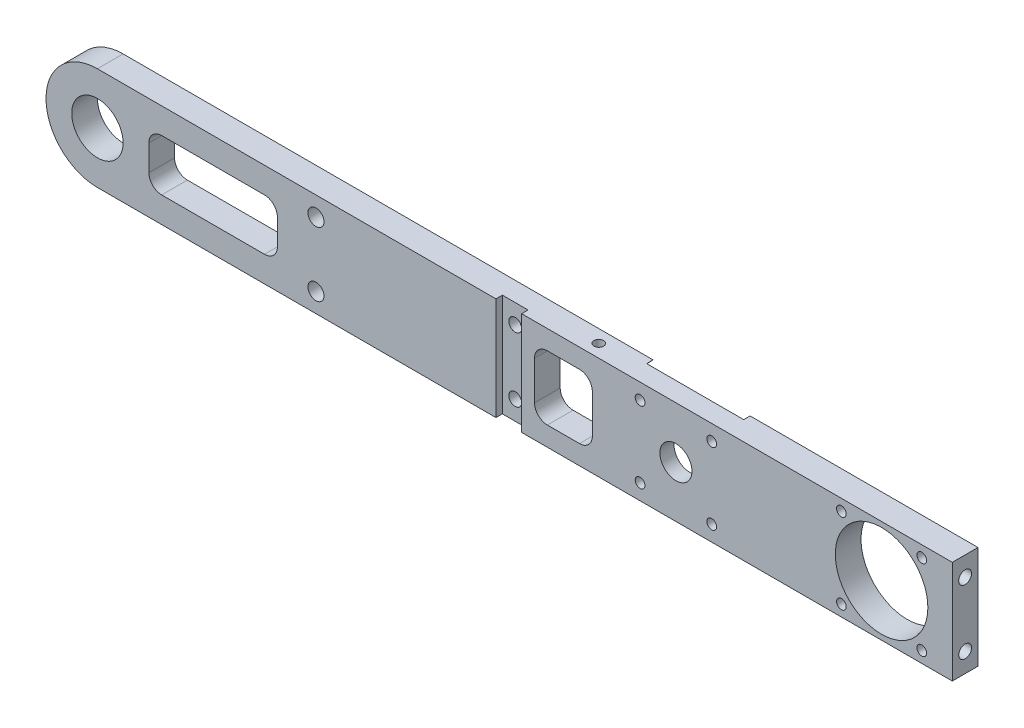
SolidWorks part; units mm, degrees
material "6061 Alloy"
ref_plane "Front Plane" through (0, 0, 0) normal (0, 0, 1) x (1, 0, 0)
ref_plane "Top Plane" through (0, 0, 0) normal (0, 1, 0) x (1, 0, 0)
ref_plane "Right Plane" through (0, 0, 0) normal (1, 0, 0) x (0, 0, -1)
sketch "Sketch1" plane through (0, 0, 0) normal (0, 0, 1) x (1, 0, 0)
  line L0 (0, 50.8) -> (-422.275, 50.8)
  line L1 (0, 50.8) -> (0, 0)
  line L2 (0, 0) -> (-422.275, 0)
  arc A0 (-422.275, 50.8) -> (-422.275, 0) centre (-422.275, 25.4) ccw
  circle A1 centre (-422.275, 25.4) radius 12.7
  circle A2 centre (-136.525, 25.4) radius 7.9375
  circle A3 centre (-34.925, 25.4) radius 22.86
  dimension "D3" = 25.4
  dimension "D6" = 15.875
  dimension "D7" = 45.72
  dimension "D1" = 50.8
  dimension "D2" = 422.275
  dimension "D4" = 136.525
  dimension "D5" = 25.4
  dimension "D8" = 34.925
  dimension "D9" = 25.4
extrude "Extrude1" add sketch "Sketch1" along normal blind 12.7
sketch "Sketch2" plane through (0, 0, 12.7) normal (0, 0, 1) x (1, 0, 0)
  line L0 (0, 50.8) -> (-422.275, 50.8) construction
  line L1 (-212.725, 50.8) -> (-225.425, 50.8)
  line L2 (-212.725, 50.8) -> (-212.725, 0)
  line L3 (-212.725, 0) -> (-225.425, 0)
  line L4 (-225.425, 50.8) -> (-225.425, 0)
  line L5 (-422.275, 0) -> (0, 0) construction
  line L6 (0, 0) -> (0, 50.8) construction
  dimension "D1" = 12.7
  dimension "D2" = 212.725
extrude "Cut-Extrude1" cut sketch "Sketch2" against normal blind 3.175
sketch "Sketch4" plane through (0, 0, 0) normal (0, 0, -1) x (-1, 0, 0)
  circle A0 centre (136.525, 25.4) radius 34.925
  dimension "D1" = 69.85
extrude "Cut-Extrude3" cut sketch "Sketch4" against normal blind 3.175
sketch "Sketch5" plane through (0, 0, 3.175) normal (0, 0, -1) x (-1, 0, 0)
  circle A0 centre (136.525, 25.4) radius 17.4625
  dimension "D1" = 34.925
extrude "Cut-Extrude4" cut sketch "Sketch5" against normal blind 2.54
sketch "Sketch6" plane through (0, 0, 12.7) normal (0, 0, 1) x (1, 0, 0)
  line L0 (0, 50.8) -> (-212.725, 50.8) construction
  line L1 (-390.525, 38.1) -> (-339.725, 38.1)
  line L2 (-396.875, 31.75) -> (-396.875, 19.05)
  line L3 (-390.525, 12.7) -> (-339.725, 12.7)
  line L4 (-333.375, 31.75) -> (-333.375, 19.05)
  line L5 (-160.4957, 50.8) -> (-422.275, 50.8) construction
  line L9 (-266.7, 41.275) -> (-238.125, 41.275)
  line L10 (-273.05, 34.925) -> (-273.05, 15.875)
  line L11 (-266.7, 9.525) -> (-238.125, 9.525)
  line L12 (-231.775, 34.925) -> (-231.775, 15.875)
  line L13 (-200.025, 41.275) -> (-184.15, 41.275)
  line L14 (-206.375, 34.925) -> (-206.375, 15.875)
  line L15 (-200.025, 9.525) -> (-184.15, 9.525)
  line L16 (-177.8, 34.925) -> (-177.8, 15.875)
  line L17 (-212.725, 0) -> (-212.725, 50.8) construction
  line L18 (-422.275, 0) -> (-225.425, 0) construction
  line L19 (-225.425, 50.8) -> (-225.425, 0) construction
  arc A0 (-184.15, 41.275) -> (-177.8, 34.925) centre (-184.15, 34.925) cw
  arc A1 (-184.15, 9.525) -> (-177.8, 15.875) centre (-184.15, 15.875) ccw
  arc A2 (-206.375, 15.875) -> (-200.025, 9.525) centre (-200.025, 15.875) ccw
  arc A3 (-200.025, 41.275) -> (-206.375, 34.925) centre (-200.025, 34.925) ccw
  arc A4 (-238.125, 41.275) -> (-231.775, 34.925) centre (-238.125, 34.925) cw
  arc A5 (-238.125, 9.525) -> (-231.775, 15.875) centre (-238.125, 15.875) ccw
  arc A6 (-273.05, 15.875) -> (-266.7, 9.525) centre (-266.7, 15.875) ccw
  arc A7 (-266.7, 41.275) -> (-273.05, 34.925) centre (-266.7, 34.925) ccw
  arc A12 (-339.725, 38.1) -> (-333.375, 31.75) centre (-339.725, 31.75) cw
  arc A13 (-339.725, 12.7) -> (-333.375, 19.05) centre (-339.725, 19.05) ccw
  arc A14 (-396.875, 19.05) -> (-390.525, 12.7) centre (-390.525, 19.05) ccw
  arc A15 (-390.525, 38.1) -> (-396.875, 31.75) centre (-390.525, 31.75) ccw
  circle A16 centre (-422.275, 25.4) radius 12.7 construction
  dimension "D5" = 6.35
  dimension "D6" = 6.35
  dimension "D14" = 25.4
  dimension "D1" = 28.575
  dimension "D2" = 31.75
  dimension "D3" = 9.525
  dimension "D4" = 6.35
  dimension "D7" = 41.275
  dimension "D8" = 31.75
  dimension "D9" = 12.7
  dimension "D10" = 25.4
  dimension "D11" = 9.525
  dimension "D12" = 6.35
  dimension "D13" = 63.5
extrude "Cut-Extrude5" cut sketch "Sketch6" against normal through all
sketch "Sketch7" plane through (0, 0, 0) normal (0, 0, -1) x (-1, 0, 0)
  line L1 (0, 0) -> (0, 50.8) construction
  line L2 (112.5543, 0) -> (0, 0) construction
  circle A0 centre (80.9625, 31.75) radius 12.7
  dimension "D1" = 25.4
  dimension "D2" = 31.75
  dimension "D3" = 80.9625
extrude "Cut-Extrude6" cut sketch "Sketch7" against normal blind 9.525
sketch "Sketch8" plane through (0, 0, 3.175) normal (0, 0, -1) x (-1, 0, 0)
  line L0 (136.525, 25.4) -> (118.8339, 43.0911) construction
  line L1 (0, 50.8) -> (112.5543, 50.8) construction
  circle A0 centre (118.8339, 43.0911) radius 2.413
  circle A2 centre (136.525, 25.4) radius 7.9375 construction
  dimension "D1" = 4.826
  dimension "D2" = 25.019
  dimension "D3" = 45
extrude "Cut-Extrude7" cut sketch "Sketch8" against normal through all
pattern_circular "CirPattern1" count 4 over 360 about axis through (-136.525, 25.4, 0) along (0, 0, 1) of "Cut-Extrude7"
sketch "Sketch9" plane through (0, 0, 0) normal (0, 0, -1) x (-1, 0, 0)
  line L0 (0, 50.8) -> (112.5543, 50.8) construction
  line L1 (0, 0) -> (0, 50.8) construction
  circle A0 centre (15.0812, 45.2437) radius 2.3812
  circle A1 centre (54.7687, 45.2437) radius 2.3812
  circle A2 centre (54.7687, 5.5562) radius 2.3812
  circle A3 centre (15.0813, 5.5562) radius 2.3813
  dimension "D1" = 4.7625
  dimension "D2" = 39.6875
  dimension "D3" = 39.6875
  dimension "D4" = 5.5562
  dimension "D5" = 15.0812
extrude "Cut-Extrude8" cut sketch "Sketch9" against normal through all
sketch "Sketch10" plane through (0, 0, 0) normal (0, 0, -1) x (-1, 0, 0)
  line L0 (160.4957, 50.8) -> (422.275, 50.8) construction
  circle A0 centre (314.325, 41.275) radius 3.9688
  circle A1 centre (314.325, 9.525) radius 3.9688
  circle A2 centre (422.275, 25.4) radius 12.7 construction
  dimension "D1" = 7.9375
  dimension "D2" = 7.9375
  dimension "D3" = 31.75
  dimension "D4" = 9.525
  dimension "D5" = 107.95
extrude "Cut-Extrude9" cut sketch "Sketch10" against normal through all
sketch "Sketch11" plane through (0, 0, 12.7) normal (0, 0, 1) x (1, 0, 0)
  line L0 (-238.125, 41.275) -> (-266.7, 41.275) construction
  line L1 (-273.05, 41.275) -> (-231.775, 41.275)
  line L2 (-273.05, 41.275) -> (-273.05, 9.525)
  line L3 (-273.05, 9.525) -> (-231.775, 9.525)
  line L4 (-231.775, 41.275) -> (-231.775, 9.525)
  line L5 (-273.05, 34.925) -> (-273.05, 15.875) construction
  line L6 (-231.775, 15.875) -> (-231.775, 34.925) construction
  line L7 (-266.7, 9.525) -> (-238.125, 9.525) construction
extrude "Extrude2" add sketch "Sketch11" against normal blind 3.175
sketch "Sketch12" plane through (0, 0, 0) normal (1, 0, 0) x (0, 0, -1)
  line L1 (-12.7, 0) -> (-12.7, 50.8) construction
  line L2 (-12.7, 50.8) -> (0, 50.8) construction
  line L3 (-12.7, 0) -> (0, 0) construction
  circle A0 centre (-6.35, 9.525) radius 3.175
  circle A1 centre (-6.35, 41.275) radius 3.175
  dimension "D1" = 6.35
  dimension "D2" = 6.35
  dimension "D3" = 6.35
  dimension "D4" = 6.35
  dimension "D5" = 9.525
  dimension "D6" = 9.525
extrude "Cut-Extrude10" cut sketch "Sketch12" against normal up to next
sketch "Sketch13" plane through (0, 0, 9.525) normal (0, 0, 1) x (1, 0, 0)
  line L0 (-212.725, 0) -> (-212.725, 50.8) construction
  line L1 (-225.425, 50.8) -> (-225.425, 0) construction
  line L2 (-212.725, 50.8) -> (-225.425, 50.8) construction
  line L3 (-225.425, 0) -> (-212.725, 0) construction
  circle A0 centre (-219.075, 41.275) radius 3.175
  circle A1 centre (-219.075, 9.525) radius 3.175
  dimension "D1" = 6.35
  dimension "D2" = 6.35
  dimension "D3" = 6.35
  dimension "D4" = 6.35
  dimension "D5" = 9.525
  dimension "D6" = 9.525
extrude "Cut-Extrude11" cut sketch "Sketch13" against normal through all
sketch "Sketch14" plane through (0, 0, 0) normal (0, 0, -1) x (-1, 0, 0)
  circle A0 centre (219.075, 41.275) radius 6.7437
  circle A1 centre (219.075, 9.525) radius 6.7437
  dimension "D1" = 13.4874
  dimension "D2" = 13.4874
extrude "Cut-Extrude12" cut sketch "Sketch14" against normal through all draft 41
sketch "Sketch15" plane through (0, 50.8, 0) normal (0, 1, 0) x (-1, 0, 0)
  line L1 (0, 12.7) -> (212.725, 12.7) construction
  line L3 (0, 12.7) -> (0, 0) construction
  circle A1 centre (180.975, 6.35) radius 2.3813
  dimension "D1" = 4.7625
  dimension "D2" = 180.975
  dimension "D5" = 6.35
extrude "Cut-Extrude13" cut sketch "Sketch15" against normal blind 15.875
sketch "Sketch16" plane through (0, 0, 0) normal (0, -1, 0) x (1, 0, 0)
  circle A1 centre (-180.975, 6.35) radius 2.3813
  circle A3 centre (-180.975, 6.35) radius 2.3813 construction
  dimension "D2" = 4.7625
extrude "Cut-Extrude14" cut sketch "Sketch16" against normal blind 15.875
sketch "Sketch17" plane through (0, 0, 0) normal (0, 0, -1) x (-1, 0, 0)
  line L0 (317.5, 50.8) -> (274.7242, 177.103)
  line L1 (160.4957, 50.8) -> (422.275, 50.8) construction
  line L2 (274.7242, 177.103) -> (250.6665, 168.9553)
  line L3 (250.6665, 168.9553) -> (271.0359, 108.811)
  line L4 (317.5, 50.8) -> (250.6665, 50.8)
  line L5 (0, 0) -> (0, 50.8) construction
  line L6 (271.0359, 108.811) -> (250.6665, 50.8)
  dimension "D1" = 317.5
  dimension "D2" = 25.4
  dimension "D3" = 71.29
  dimension "D4" = 133.35
  dimension "D5" = 63.5
extrude "Extrude3" [suppressed] add sketch "Sketch17" against normal up to surface (12.7 mm away)
sketch "Sketch18" [suppressed] plane through (0, 0, 0) normal (0, 0, -1) x (-1, 0, 0)
  line L0 (284.4698, 108.7362) -> (264.1267, 50.8)
  line L1 (264.1267, 50.8) -> (304.0914, 50.8)
  line L2 (304.0914, 50.8) -> (284.4698, 108.7362)
  line L3 (317.5, 50.8) -> (274.7242, 177.103) construction
  line L4 (271.0359, 108.811) -> (250.6665, 50.8) construction
  line L5 (317.5, 50.8) -> (422.275, 50.8) construction
  dimension "D1" = 12.7
  dimension "D2" = 12.7
extrude "Cut-Extrude15" [suppressed] cut sketch "Sketch18" against normal through all
ref_plane "Plane1" through (0, 25.4, 0) normal (0, 1, 0) x (-1, 0, 0)
mirror "Mirror6" [suppressed] about plane through (0, 25.4, 0) normal (0, 1, 0)
fillet "Fillet1" [suppressed] radius 25.4
fillet "Fillet2" [suppressed] radius 12.7
fillet "Fillet4" [suppressed] radius 6.35
fillet "Fillet3" [suppressed] radius 12.7
sketch "Sketch19" [suppressed] plane through (0, 0, 0) normal (0, 0, -1) x (-1, 0, 0)
  line L0 (271.717, -125.2846) -> (253.6737, -119.1737) construction
  line L1 (254.7404, -106.1264) -> (268.2258, -66.3083) construction
  line L2 (271.717, 176.0846) -> (253.6737, 169.9737) construction
  line L3 (311.6571, 68.0522) -> (278.7981, 165.0742) construction
  circle A0 centre (266.7692, 161.0003) radius 3.9688
  circle A1 centre (266.7692, -110.2003) radius 3.9688
  dimension "D1" = 7.9375
  dimension "D2" = 7.9375
  dimension "D3" = 12.7
  dimension "D4" = 12.7
  dimension "D5" = 12.7
  dimension "D6" = 12.7
extrude "Cut-Extrude16" [suppressed] cut sketch "Sketch19" against normal through all
